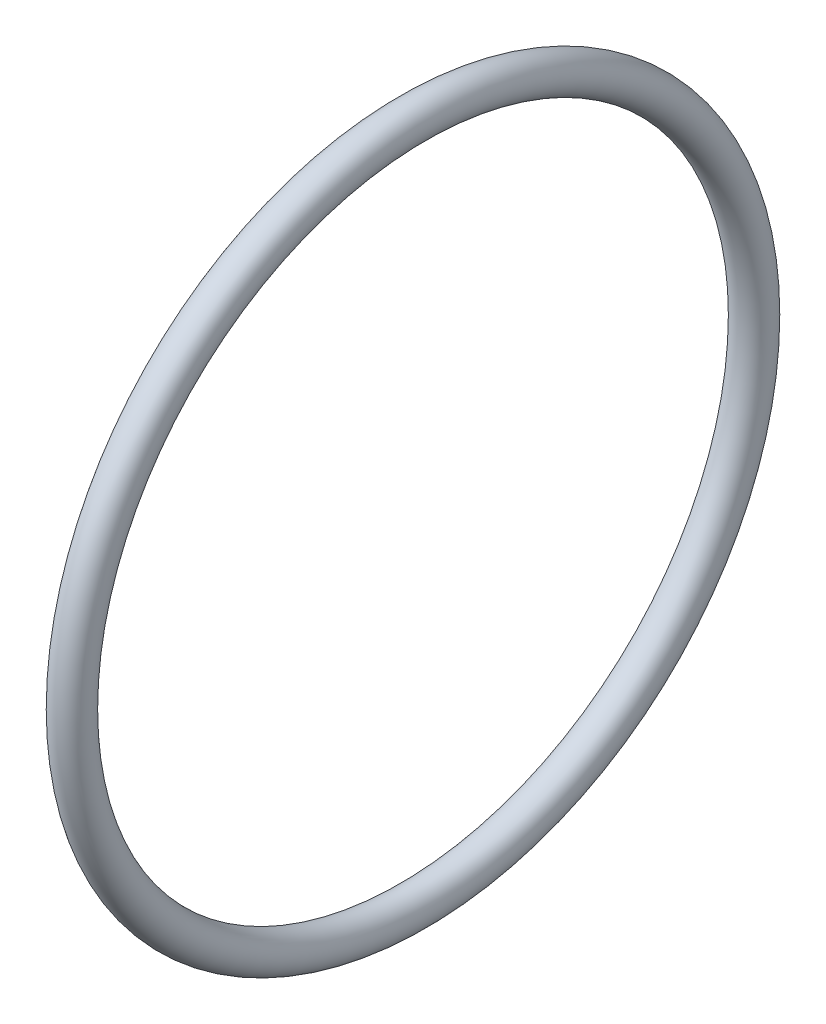
SolidWorks part; units mm, degrees
material "ﾆﾄﾘﾙｺﾞﾑ(NBR)"
ref_plane "正面" through (0, 0, 0) normal (0, 0, 1) x (1, 0, 0)
ref_plane "平面" through (0, 0, 0) normal (0, 1, 0) x (1, 0, 0)
ref_plane "右側面" through (0, 0, 0) normal (1, 0, 0) x (0, 0, -1)
sketch "ｽｹｯﾁ3" plane through (0, 0, 0) normal (1, 0, 0) x (0, 0, -1)
  line L0 (0, 12.5) -> (0, -12.5) construction
  line L1 (11.3923, 12.5) -> (11.3923, -12.5)
  line L2 (-11.3923, 12.5) -> (-11.3923, -12.5)
  arc A0 (11.3923, 12.5) -> (-11.3923, 12.5) centre (0, 12.5) ccw
  arc A1 (-11.3923, -12.5) -> (11.3923, -12.5) centre (0, -12.5) ccw
  point P2 (0, 0)
sketch "ｽｹｯﾁ1" plane through (0, 0, 0) normal (0, 0, 1) x (1, 0, 0)
  line L0 (0, 0) -> (50000, 0) construction
  circle A0 centre (0, 18.75) radius 1
  dimension "D1" = 2
  dimension "D2" = 35.5
sketch "ｽｹｯﾁ4" plane through (0, 0, 0) normal (0, 0, 1) x (1, 0, 0)
  line L0 (-0.75, 25.2423) -> (-0.75, 22.5423) construction
  line L1 (-0.75, 22.5423) -> (0.75, 22.5423) construction
  line L2 (0.75, 22.5423) -> (0.75, 25.2423) construction
  line L3 (0.75, 25.2423) -> (-0.75, 25.2423) construction
  line L4 (-0.75, 23.8923) -> (0.75, 23.8923) construction
  ellipse E0 centre (0, 23.8923) end of major axis (0, 25.1823) minor radius 0.75
  point P4 (0, 22.5423)
  point P8 (0, 23.8923)
  dimension "D1" = 1.5
  dimension "D2" = 2.7
  dimension "D3" = 2.58
sweep "ｽｲｰﾌﾟ2" [suppressed] add profiles "ｽｹｯﾁ4" path "ｽｹｯﾁ3"
revolve "回転1" add sketch "ｽｹｯﾁ1" angle 360 about L0
equation "\"オーリング内径35.5mm\"= 36"
equation "\"オーリング周長\"= \"オーリング内径35.5mm\" * pi"
